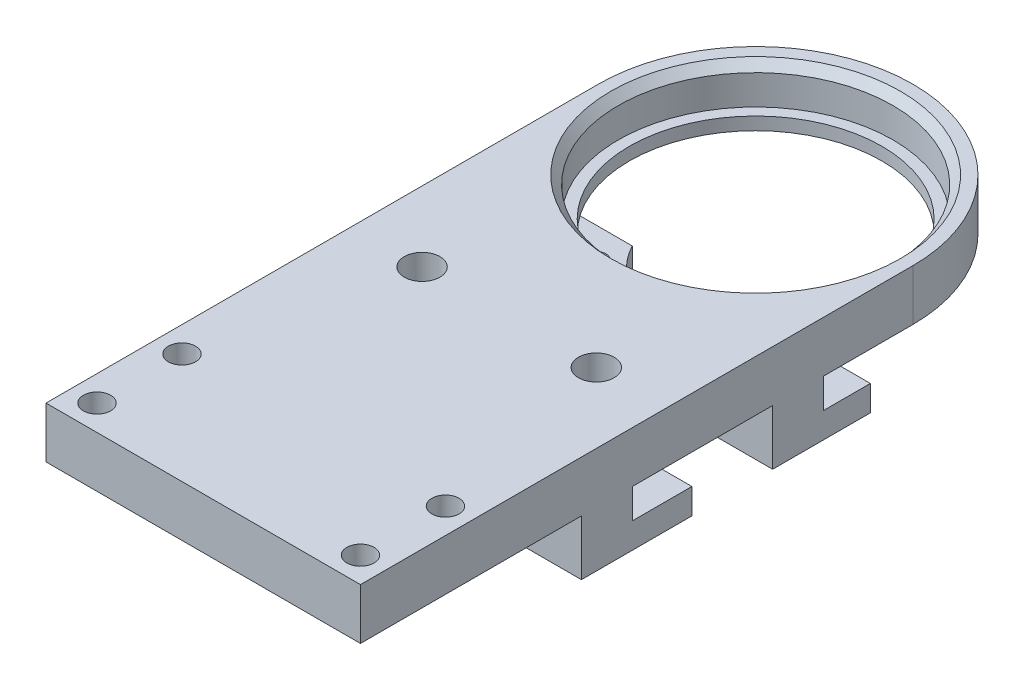
SolidWorks part; units mm, degrees
ref_plane "정면" through (0, 0, 0) normal (0, 0, 1) x (1, 0, 0)
ref_plane "윗면" through (0, 0, 0) normal (0, 1, 0) x (1, 0, 0)
ref_plane "우측면" through (0, 0, 0) normal (1, 0, 0) x (0, 0, -1)
sketch "스케치1" plane through (0, 0, 0) normal (0, 1, 0) x (1, 0, 0)
  line L2 (-18.5, 0) -> (-18.5, -65)
  line L3 (-18.5, -65) -> (18.5, -65)
  line L4 (18.5, 0) -> (18.5, -65)
  arc A0 (18.5, 0) -> (-18.5, 0) centre (0, 0) ccw
  dimension "D1" = 37
  dimension "D2" = 65
extrude "보스-돌출1" add sketch "스케치1" along normal blind 6
sketch "스케치2" plane through (0, 6, 0) normal (0, 1, 0) x (1, 0, 0)
  circle A0 centre (0, 0) radius 16.15
  dimension "D1" = 32.3
extrude "컷-돌출1" cut sketch "스케치2" against normal blind 4.5
sketch "스케치3" plane through (0, 1.5, 0) normal (0, 1, 0) x (1, 0, 0)
  circle A0 centre (0, 0) radius 14.85
  circle A1 centre (0, 0) radius 16.15 construction
  dimension "D1" = 1.3
extrude "컷-돌출2" cut sketch "스케치3" against normal through all
chamfer "모따기1" distance 1 angle 42 1 edges at (0, 6, 16.15)
sketch "스케치4" plane through (0, 0, 0) normal (0, -1, 0) x (1, 0, 0)
  line L0 (-18.5, 0) -> (-18.5, 65) construction
  line L1 (-18.5, 39) -> (18.5, 39)
  line L2 (-18.5, 39) -> (-18.5, 33)
  line L3 (-18.5, 33) -> (18.5, 33)
  line L4 (18.5, 39) -> (18.5, 33)
  line L5 (18.5, 65) -> (18.5, 0) construction
  line L11 (-18.5, 16.5) -> (-10.5, 16.5)
  line L12 (-18.5, 16.5) -> (-18.5, 10.5)
  line L13 (-18.5, 10.5) -> (-13.3697, 10.5)
  line L14 (-10.5, 16.5) -> (-10.5, 13.3697)
  line L15 (18.5, 16.5) -> (10.5, 16.5)
  line L16 (18.5, 16.5) -> (18.5, 10.5)
  line L17 (18.5, 10.5) -> (13.3697, 10.5)
  line L18 (10.5, 16.5) -> (10.5, 13.3697)
  circle A0 centre (0, 0) radius 14.85 construction
  arc A2 (-10.5, 13.3697) -> (-13.3697, 10.5) centre (0, 0) ccw
  arc A3 (13.3697, 10.5) -> (10.5, 13.3697) centre (0, 0) ccw
  dimension "D5" = 16.5
  dimension "D6" = 34
  dimension "D1" = 6
  dimension "D2" = 33
  dimension "D3" = 6
  dimension "D4" = 8
extrude "보스-돌출2" add sketch "스케치4" along normal blind 6.5
sketch "스케치5" plane through (0, -6.5, 0) normal (0, -1, 0) x (1, 0, 0)
  line L0 (-18.5, 33) -> (18.5, 33) construction
  line L1 (-7.15, 33) -> (7.15, 33)
  line L2 (-7.15, 33) -> (-7.15, 35.8)
  line L3 (-7.15, 35.8) -> (7.15, 35.8)
  line L4 (7.15, 33) -> (7.15, 35.8)
  line L5 (18.5, 39) -> (-18.5, 39) construction
  point P8 (0, 39)
  dimension "D1" = 3.2
  dimension "D2" = 14.3
  dimension "D3" = 7.15
extrude "컷-돌출3" cut sketch "스케치5" against normal blind 1.5
sketch "스케치6" plane through (0, 0, 33) normal (0, 0, -1) x (-1, 0, 0)
  line L0 (-7.15, -5) -> (-7.15, -6.5) construction
  line L1 (-18.5, -6.5) -> (-7.15, -6.5)
  line L2 (-18.5, -6.5) -> (-18.5, -3.5)
  line L3 (-18.5, -3.5) -> (-7.15, -3.5)
  line L4 (-7.15, -6.5) -> (-7.15, -3.5)
  line L5 (18.5, -6.5) -> (7.15, -6.5)
  line L6 (18.5, -6.5) -> (18.5, -3.5)
  line L7 (18.5, -3.5) -> (7.15, -3.5)
  line L8 (7.15, -6.5) -> (7.15, -3.5)
  line L9 (7.15, -5) -> (7.15, -6.5) construction
  dimension "D1" = 3
extrude "보스-돌출3" add sketch "스케치6" along normal blind 28
sketch "스케치7" plane through (0, -6.5, 0) normal (0, -1, 0) x (1, 0, 0)
  line L0 (7.15, 35.8) -> (-7.15, 35.8) construction
  line L1 (-10.25, 29) -> (10.25, 29) construction
  line L2 (-10.25, 29) -> (-10.25, 8.5) construction
  line L3 (-10.25, 8.5) -> (10.25, 8.5) construction
  line L4 (10.25, 29) -> (10.25, 8.5) construction
  circle A1 centre (0, 0) radius 14.85 construction
  circle A2 centre (-10.25, 29) radius 1.15
  circle A3 centre (10.25, 29) radius 1.15
  circle A4 centre (-10.25, 8.5) radius 1.15
  circle A5 centre (10.25, 8.5) radius 1.15
  dimension "D1" = 20.5
  dimension "D5" = 2.3
  dimension "D2" = 20.5
  dimension "D3" = 6.8
  dimension "D4" = 10.25
extrude "컷-돌출4" cut sketch "스케치7" against normal through all
sketch "스케치8" plane through (0, 6, 0) normal (0, 1, 0) x (1, 0, 0)
  circle A0 centre (-10.25, -29) radius 2.1
  circle A1 centre (10.25, -29) radius 2.1
  dimension "D1" = 4.2
extrude "컷-돌출5" cut sketch "스케치8" against normal up to next
sketch "스케치9" plane through (0, -6.5, 0) normal (0, -1, 0) x (1, 0, 0)
  line L0 (-18.5, 39) -> (-18.5, 5) construction
  line L1 (-18.5, 26) -> (18.5, 26)
  line L2 (-18.5, 26) -> (-18.5, 16.5)
  line L3 (-18.5, 16.5) -> (18.5, 16.5)
  line L4 (18.5, 26) -> (18.5, 16.5)
  line L5 (18.5, 5) -> (18.5, 39) construction
  line L6 (18.5, 16.5) -> (10.5, 16.5) construction
  circle A0 centre (10.25, 29) radius 1.15 construction
  circle A1 centre (0, 0) radius 10.75
  dimension "D2" = 21.5
  dimension "D1" = 3
extrude "컷-돌출6" cut sketch "스케치9" against normal up to next
sketch "스케치10" plane through (0, 6, 0) normal (0, 1, 0) x (1, 0, 0)
  line L0 (-18.5, -65) -> (18.5, -65) construction
  line L1 (-15.5, -52) -> (15.5, -52) construction
  line L2 (-15.5, -52) -> (-15.5, -62) construction
  line L3 (-15.5, -62) -> (15.5, -62) construction
  line L4 (15.5, -52) -> (15.5, -62) construction
  line L5 (18.5, -65) -> (18.5, 0) construction
  line L6 (-18.5, 0) -> (-18.5, -65) construction
  circle A0 centre (-15.5, -52) radius 1.6
  circle A1 centre (15.5, -52) radius 1.6
  circle A2 centre (15.5, -62) radius 1.6
  circle A3 centre (-15.5, -62) radius 1.6
  dimension "D5" = 3.2
  dimension "D1" = 3
  dimension "D2" = 3
  dimension "D3" = 3
  dimension "D4" = 10
extrude "컷-돌출7" cut sketch "스케치10" against normal up to next
chamfer "모따기2" distance 1 angle 42 4 edges at (15.5, 0, 63.6) (15.5, 0, 53.6) (-15.5, 0, 53.6) (-15.5, 0, 63.6)
